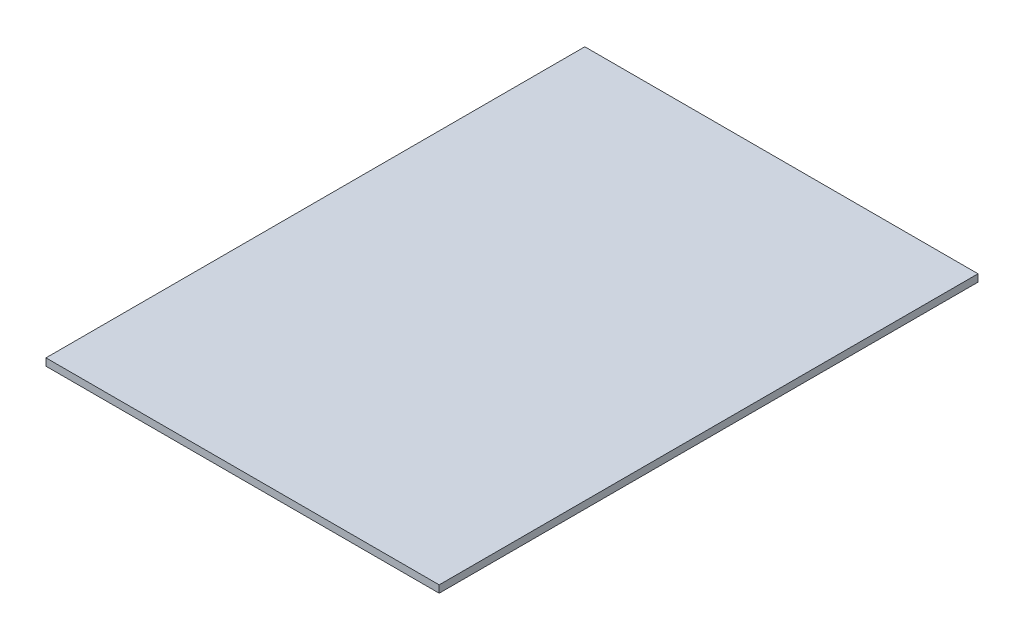
SolidWorks part; units mm, degrees
ref_plane "Front Plane" through (0, 0, 0) normal (0, 0, 1) x (1, 0, 0)
ref_plane "Top Plane" through (0, 0, 0) normal (0, 1, 0) x (1, 0, 0)
ref_plane "Right Plane" through (0, 0, 0) normal (1, 0, 0) x (0, 0, -1)
sketch "Sketch1" plane through (0, 0, 0) normal (0, 1, 0) x (1, 0, 0)
  line L1 (0, 0) -> (270, 0)
  line L2 (0, 0) -> (0, 370)
  line L3 (0, 370) -> (270, 370)
  line L4 (270, 0) -> (270, 370)
  dimension "D1" = 270
  dimension "D2" = 370
extrude "Boss-Extrude1" add sketch "Sketch1" along normal blind 5
